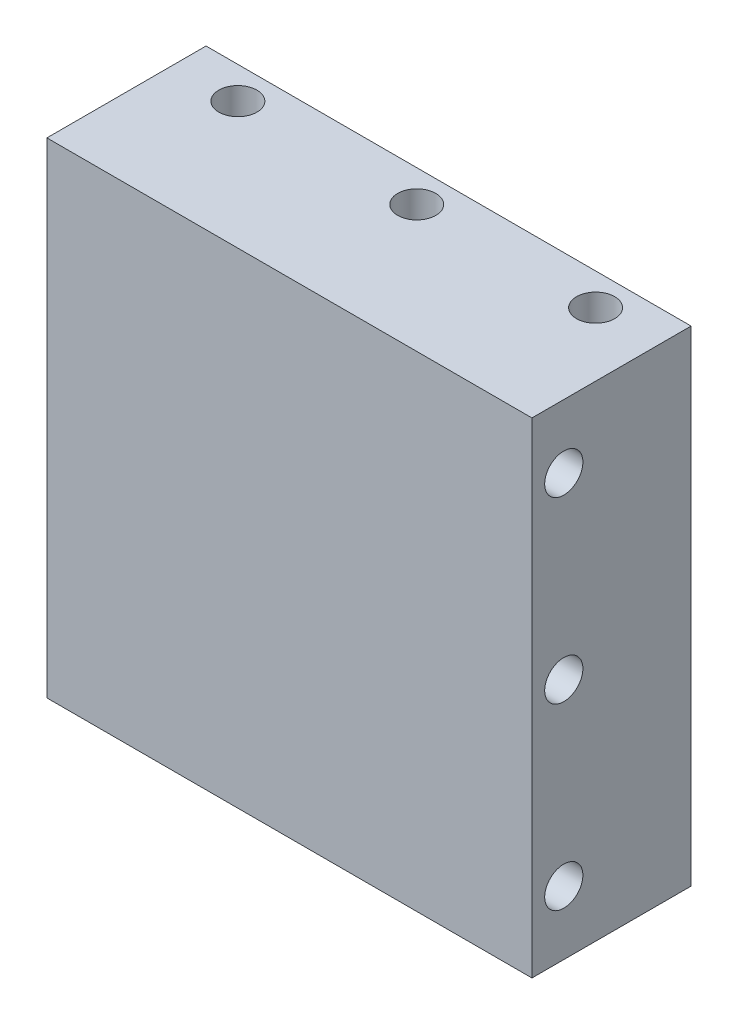
SolidWorks part; units mm, degrees
ref_plane "Front Plane" through (0, 0, 0) normal (0, 0, 1) x (1, 0, 0)
ref_plane "Top Plane" through (0, 0, 0) normal (0, 1, 0) x (1, 0, 0)
ref_plane "Right Plane" through (0, 0, 0) normal (1, 0, 0) x (0, 0, -1)
sketch "Sketch1" plane through (0, 0, 0) normal (0, 0, 1) x (1, 0, 0)
  line L1 (-76.2, 76.2) -> (76.2, 76.2)
  line L2 (-76.2, 76.2) -> (-76.2, -76.2)
  line L3 (-76.2, -76.2) -> (76.2, -76.2)
  line L4 (76.2, 76.2) -> (76.2, -76.2)
  line L5 (-76.2, 76.2) -> (76.2, -76.2) construction
  line L6 (-76.2, -76.2) -> (76.2, 76.2) construction
  point P0 (0, 0)
  dimension "D1" = 152.4
extrude "Boss-Extrude1" add sketch "Sketch1" along normal blind 50
sketch "Sketch2" plane through (76.2, 0, 0) normal (1, 0, 0) x (0, 0, -1)
  line L0 (-50, -76.2) -> (-50, 76.2) construction
  line L1 (-50, 76.2) -> (0, 76.2) construction
  line L2 (-50, -76.2) -> (0, -76.2) construction
  circle A0 centre (-40, 56.2) radius 6
  circle A1 centre (-40, 0) radius 6
  circle A2 centre (-40, -56.2) radius 6
  dimension "D1" = 10
  dimension "D2" = 10
  dimension "D3" = 10
  dimension "D4" = 20
  dimension "D5" = 20
  dimension "D6" = 112.4
  dimension "D7" = 56.2
extrude "Cut-Extrude1" cut sketch "Sketch2" against normal through all
sketch "Sketch4" plane through (0, 76.2, 0) normal (0, 1, 0) x (1, 0, 0)
  line L0 (76.2, 0) -> (-76.2, 0) construction
  line L1 (-76.2, -50) -> (-76.2, 0) construction
  line L2 (76.2, -50) -> (76.2, 0) construction
  circle A0 centre (-56.2, -10) radius 6
  circle A1 centre (0, -10) radius 6
  circle A2 centre (56.2, -10) radius 6
  dimension "D1" = 12
  dimension "D2" = 10
  dimension "D3" = 20
  dimension "D4" = 20
  dimension "D5" = 10
  dimension "D6" = 10
  dimension "D7" = 112.4
  dimension "D8" = 56.2
extrude "Cut-Extrude2" cut sketch "Sketch4" against normal through all
